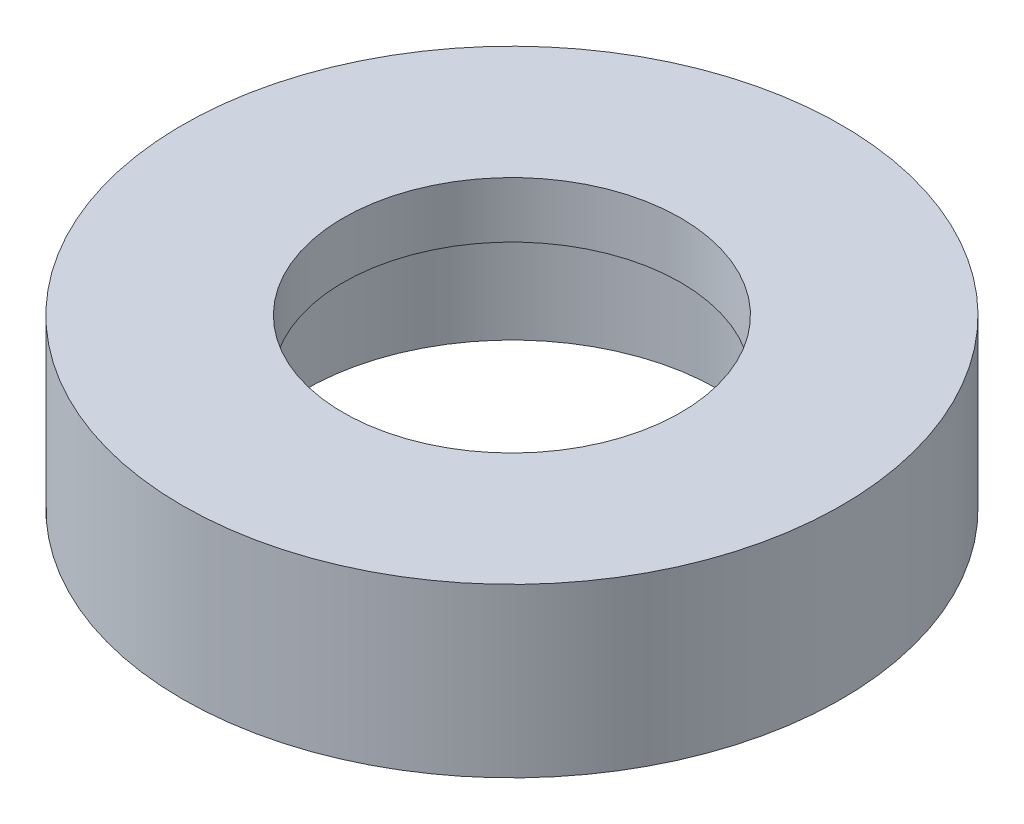
SolidWorks part; units mm, degrees
ref_plane "Front Plane" through (0, 0, 0) normal (0, 0, 1) x (1, 0, 0)
ref_plane "Top Plane" through (0, 0, 0) normal (0, 1, 0) x (1, 0, 0)
ref_plane "Right Plane" through (0, 0, 0) normal (1, 0, 0) x (0, 0, -1)
sketch "Sketch1" plane through (0, 0, 0) normal (0, 1, 0) x (1, 0, 0)
  circle A0 centre (0, 0) radius 29.5
extrude "Boss-Extrude1" add sketch "Sketch1" along normal blind 15
sketch "Sketch2" plane through (0, 0, 0) normal (0, -1, 0) x (1, 0, 0)
  circle A0 centre (0, 0) radius 15.1
extrude "Cut-Extrude1" cut sketch "Sketch2" against normal through all
sketch "Sketch3" plane through (0, 0, 0) normal (0, -1, 0) x (1, 0, 0)
  circle A0 centre (0, 0) radius 18.5
extrude "Cut-Extrude2" cut sketch "Sketch3" against normal blind 10
sketch "Sketch4" plane through (0, 0, 0) normal (0, -1, 0) x (1, 0, 0)
  circle A0 centre (21.4064, 8.8194) radius 6
extrude "Cut-Extrude3" cut sketch "Sketch4" against normal blind 10.5
